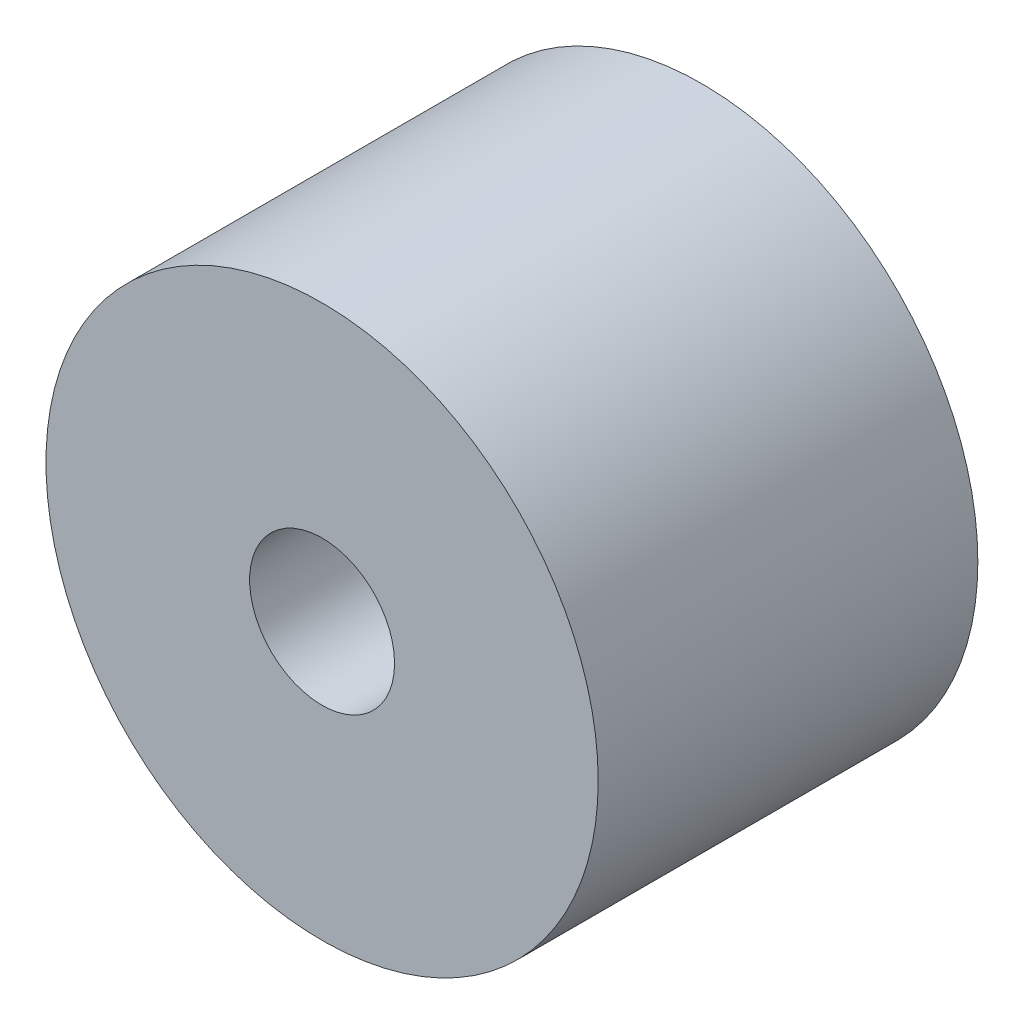
SolidWorks part; units mm, degrees
material "ﾁｰｸ材"
ref_plane "正面" through (0, 0, 0) normal (0, 0, 1) x (1, 0, 0)
ref_plane "平面" through (0, 0, 0) normal (0, 1, 0) x (1, 0, 0)
ref_plane "右側面" through (0, 0, 0) normal (1, 0, 0) x (0, 0, -1)
sketch "ｽｹｯﾁ1" plane through (0, 0, 0) normal (0, 0, 1) x (1, 0, 0)
  circle A0 centre (0, 0) radius 4
  circle A1 centre (0, 0) radius 1.05
  dimension "D1" = 2.1
  dimension "D2" = 8
extrude "ﾎﾞｽ - 押し出し1" add sketch "ｽｹｯﾁ1" along normal blind 5.5
